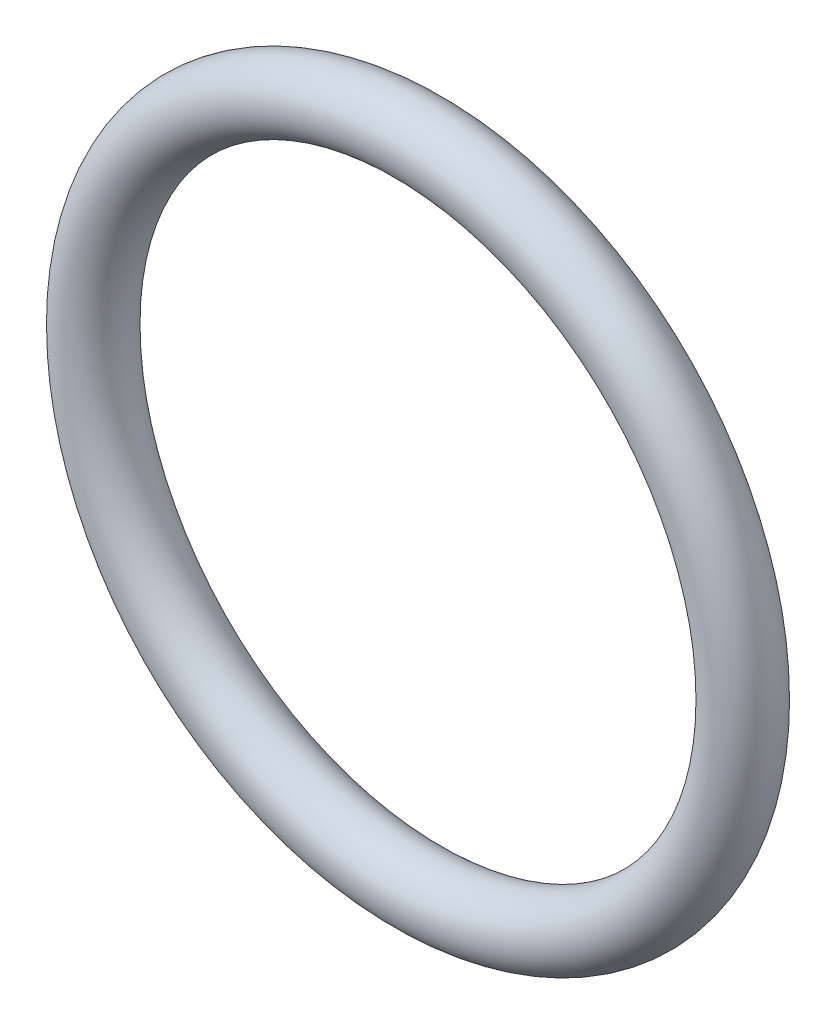
SolidWorks part; units mm, degrees
ref_plane "Front Plane" through (0, 0, 0) normal (0, 0, 1) x (1, 0, 0)
ref_plane "Top Plane" through (0, 0, 0) normal (0, 1, 0) x (1, 0, 0)
ref_plane "Right Plane" through (0, 0, 0) normal (1, 0, 0) x (0, 0, -1)
ref_axis "Axis1" through (0, 0, 0.88) along (0, 0, -1)
sketch "Sketch1" plane through (0, 0, 0) normal (1, 0, 0) x (0, 0, -1)
  circle A0 centre (0, 7.85) radius 0.8
revolve "Revolve1" add sketch "Sketch1" angle 360 about axis through (0, 0, 0.88) along (0, 0, -1)
